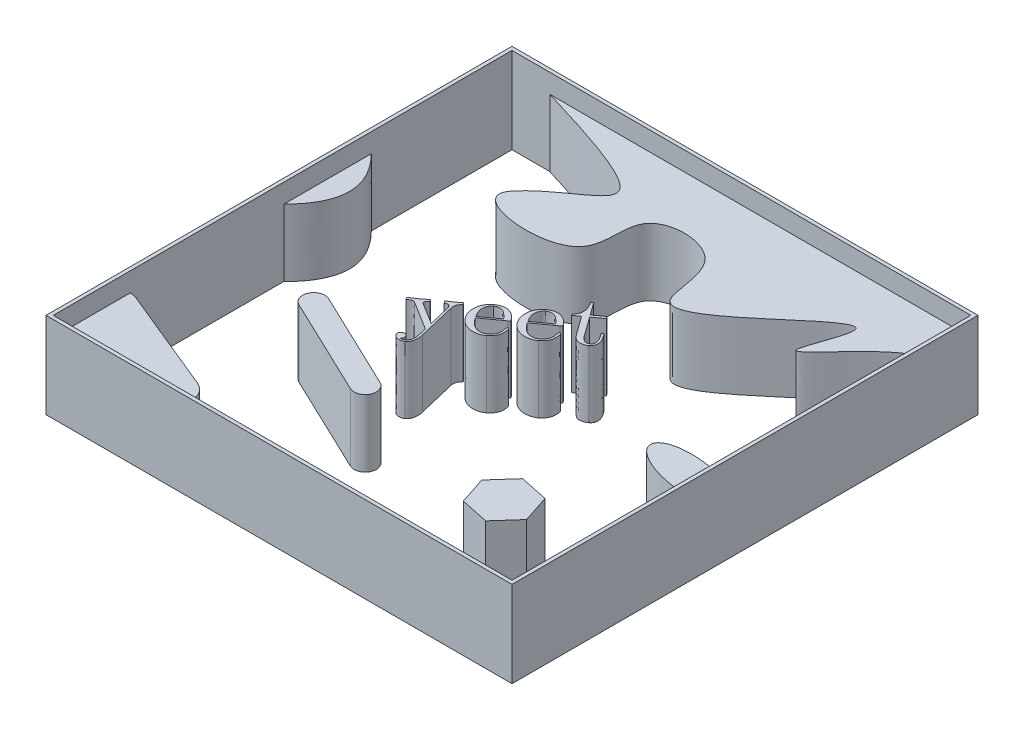
SolidWorks part; units mm, degrees
material "Maple"
ref_plane "Front Plane" through (0, 0, 0) normal (0, 0, 1) x (1, 0, 0)
ref_plane "Top Plane" through (0, 0, 0) normal (0, 1, 0) x (1, 0, 0)
ref_plane "Right Plane" through (0, 0, 0) normal (1, 0, 0) x (0, 0, -1)
sketch "Sketch1" plane through (0, 0, 0) normal (0, 1, 0) x (1, 0, 0)
  line L0 (-2476.5, 2476.5) -> (2476.5, 2476.5)
  line L1 (-2438.4, -2438.4) -> (2438.4, -2438.4)
  line L2 (-2438.4, -2438.4) -> (-2438.4, 2438.4)
  line L3 (-2438.4, 2438.4) -> (2438.4, 2438.4)
  line L4 (2438.4, -2438.4) -> (2438.4, 2438.4)
  line L5 (-2438.4, -2438.4) -> (2438.4, 2438.4) construction
  line L6 (-2438.4, 2438.4) -> (2438.4, -2438.4) construction
  line L7 (2476.5, -2476.5) -> (2476.5, 2476.5)
  line L8 (-2476.5, -2476.5) -> (2476.5, -2476.5)
  line L9 (-2476.5, -2476.5) -> (-2476.5, 2476.5)
  point P0 (0, 0)
  dimension "D1" = 4876.8
  dimension "D2" = 4876.8
  dimension "D3" = 38.1
extrude "Boss-Extrude1" add sketch "Sketch1" along normal blind 914.4
sketch "Sketch3" plane through (0, 0, 0) normal (0, 1, 0) x (1, 0, 0)
  line L0 (-276.1638, -219.5815) -> (-142.8305, -219.5815) construction
  line L44 (2438.4, 2438.4) -> (-2438.4, 2438.4) construction
  line L45 (2438.4, -2438.4) -> (2438.4, 2438.4) construction
  line L46 (-1382.4335, -724.4253) -> (-336.9162, -1223.0566) construction
  line L47 (-1331.5223, -617.6761) -> (-286.0051, -1116.3074)
  line L48 (-1433.3446, -831.1745) -> (-387.8274, -1329.8058)
  line L50 (-2438.4, 2438.4) -> (-2438.4, -2438.4) construction
  line L51 (1754.1182, -1598.9109) -> (1657.9741, -1306.7807)
  line L52 (1657.9741, -1306.7807) -> (1356.9099, -1243.9788)
  line L53 (1356.9099, -1243.9788) -> (1151.9897, -1473.3071)
  line L54 (1151.9897, -1473.3071) -> (1248.1338, -1765.4374)
  line L55 (1248.1338, -1765.4374) -> (1549.1981, -1828.2393)
  line L56 (1549.1981, -1828.2393) -> (1754.1182, -1598.9109)
  line L57 (-2438.4, -1828.2393) -> (-1331.5223, -2284.0165) construction
  line L58 (2438.4, 755.3686) -> (2212.0527, 755.3686)
  line L59 (2438.4, 755.3686) -> (2438.4, -159.0132)
  line L60 (2438.4, -159.0132) -> (2212.0527, -159.0132)
  line L61 (2212.0527, 755.3686) -> (2212.0527, -159.0132)
  line L62 (-2359.0638, -1635.5674) -> (-1252.1861, -2091.3447)
  line L64 (-2438.4, 942.8926) -> (-2438.4, 15.6298)
  line L65 (-2438.4, -2438.4) -> (-1191.5852, -2438.4)
  line L66 (2438.4, -159.0132) -> (2438.4, 755.3686)
  line L67 (2438.4, 2438.4) -> (-2033.8711, 2438.4)
  line L68 (-2438.4, -1619.8726) -> (-2438.4, -2438.4)
  line L69 (2438.4, 1945.6649) -> (2438.4, 2438.4)
  arc A0 (-1331.5223, -617.6761) -> (-1433.3446, -831.1745) centre (-1382.4335, -724.4253) ccw
  arc A1 (-387.8274, -1329.8058) -> (-286.0051, -1116.3074) centre (-336.9162, -1223.0566) ccw
  circle A2 centre (1453.054, -1536.109) radius 266.3415 construction
  arc A3 (-2359.0638, -1635.5674) -> (-2438.4, -1619.8726) centre (-2438.4, -1828.2393) ccw
  arc A4 (-1191.5852, -2438.4) -> (-1252.1861, -2091.3447) centre (-1331.5223, -2284.0165) ccw
  parabola Q0 (-2438.4, 942.8926) -> (-2438.4, 15.6298) focus (-2438.4, 479.2612) apex (-2206.5843, 479.2612)
  spline S0 degree 3 poles (-2033.8711, 2438.4) (-132.861, 1869.4822) (-884.0388, 1875.1225) (-1598.1447, 1067.8657) (-185.8693, 912.31) (-553.0617, 1926.6051) (493.2178, 1908.9137) (381.7827, 899.4613) (1122.8897, 1447.8201) (1961.4171, 2223.6534) (1328.2558, 822.275) (2273.4726, 2188.7601) (2438.4, 1945.6649) knots 0 0 0 0 0.232883 0.254081 0.374414 0.450762 0.536671 0.613759 0.711876 0.803327 0.869143 1 1 1 1
  point P8 (-859.6748, -973.7409)
  point P51 (-1884.9611, -2056.1279)
  point P55 (-1103.7906, 977.7179)
  point P60 (-191.1533, 1113.8571)
  point P61 (131.5471, -776.9659)
  point P65 (-473.6377, -771.9237)
  point P66 (232.2387, -262.6621)
  point P67 (756.7793, 302.0638)
  point P68 (-680.2462, -724.4253)
  point P69 (0, 0)
  point P70 (0, 0)
  point P71 (2212.0527, -159.0132)
extrude "Boss-Extrude2" add sketch "Sketch3" along normal blind 711.2 and the other way blind 2.54 contours S0 L69 L67 | Q0 L64 | L47 A1 L48 A0 | L62 A4 L65 L68 A3 | L55 L56 L51 L52 L53 L54
sketch "Sketch5" plane through (0, 0, 0) normal (0, 1, 0) x (1, 0, 0)
  line L0 (-718.5128, -513.2445) -> (718.5128, 513.2445) construction
  line L1 (2438.4, -191.102) -> (2438.4, -523.6086)
  line L3 (2438.4, -2438.4) -> (2438.4, 1945.6649) construction
  ellipse E0 centre (2207.0423, -322.1795) end of major axis (2691.8285, -408.6299) minor radius 186.549 (2438.4, -191.102) -> (2438.4, -523.6086) ccw
  text T0 "yeet" font "CMU Serif" height 609.6
  point P11 (0, 0)
extrude "Boss-Extrude3" add sketch "Sketch5" along normal up to surface (711.2 mm away) separate body up to face at (202.2644, 711.2, -2356.2775)
